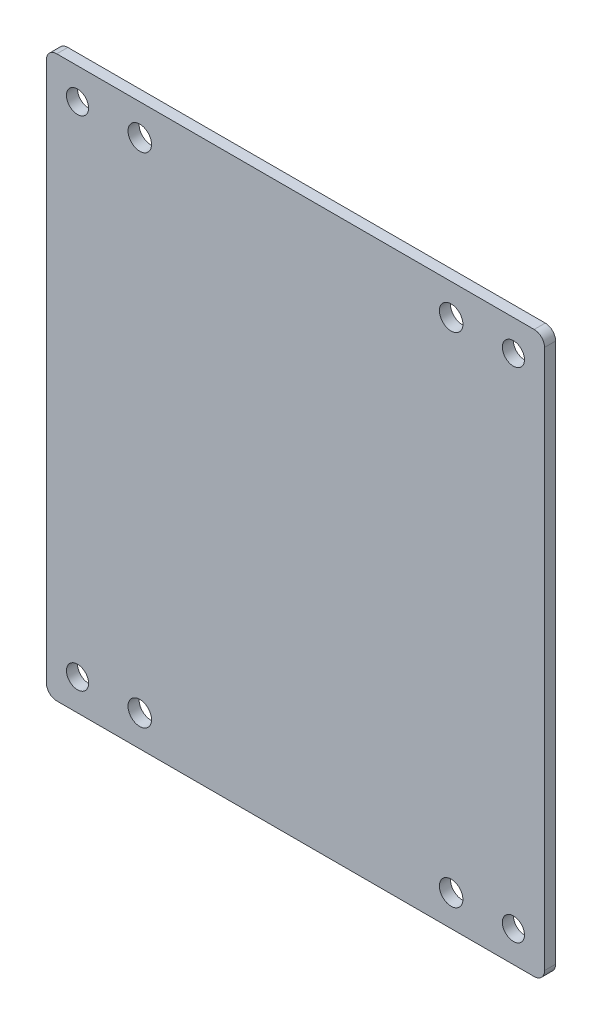
SolidWorks part; units mm, degrees
ref_plane "Alzado" through (0, 0, 0) normal (0, 0, 1) x (1, 0, 0)
ref_plane "Planta" through (0, 0, 0) normal (0, 1, 0) x (1, 0, 0)
ref_plane "Vista lateral" through (0, 0, 0) normal (1, 0, 0) x (0, 0, -1)
sketch "Model" plane through (0, 0, 0) normal (0, 0, 1) x (1, 0, 0)
  line L0 (79.0698, 220.6038) -> (79.0698, 298.6084)
  line L1 (7.0674, 298.6084) -> (7.0674, 220.6038)
  line L2 (8.5674, 219.1038) -> (77.5698, 219.1038)
  line L3 (77.5698, 300.1084) -> (8.5674, 300.1084)
  line L4 (76.4432, 280.3563) -> (73.4432, 280.3563)
  line L5 (76.4432, 232.4763) -> (76.4432, 280.3563)
  line L6 (73.4432, 232.4763) -> (76.4432, 232.4763)
  line L7 (73.4432, 280.3563) -> (73.4432, 232.4763)
  line L8 (28.1808, 232.4801) -> (28.1808, 271.1578)
  line L9 (25.1808, 232.4801) -> (28.1808, 232.4801)
  line L10 (25.1808, 271.1578) -> (25.1808, 232.4801)
  line L11 (9.2551, 269.0104) -> (9.2563, 226.8832)
  line L12 (18.685, 269.0104) -> (18.6863, 226.8832)
  line L13 (18.685, 269.0104) -> (9.2551, 269.0104)
  line L14 (18.6863, 226.8832) -> (9.2563, 226.8832)
  line L15 (37.929, 268.6584) -> (37.9301, 275.5694)
  line L16 (41.2725, 268.3584) -> (38.2289, 268.3584)
  line L17 (41.5725, 277.3009) -> (41.5725, 268.6584)
  line L18 (38.6121, 277.6009) -> (41.2725, 277.6009)
  line L19 (47.8995, 221.0056) -> (62.2048, 221.0056)
  line L20 (62.2048, 228.2055) -> (47.8995, 228.2055)
  line L21 (47.8995, 228.2055) -> (47.8995, 221.0056)
  line L22 (62.2048, 221.0056) -> (62.2048, 228.2055)
  line L23 (28.1941, 221.0056) -> (42.2994, 221.0056)
  line L24 (42.2994, 228.2055) -> (28.1941, 228.2055)
  line L25 (28.1941, 228.2055) -> (28.1941, 221.0056)
  line L26 (42.2994, 221.0056) -> (42.2994, 228.2055)
  line L27 (16.6077, 273.8998) -> (11.5077, 273.8998)
  line L28 (16.6077, 270.7998) -> (16.6077, 273.8998)
  line L29 (11.5077, 270.7998) -> (16.6077, 270.7998)
  line L30 (11.5077, 273.8998) -> (11.5077, 270.7998)
  line L31 (16.6077, 281.0451) -> (11.5077, 281.0451)
  line L32 (16.6077, 277.9451) -> (16.6077, 281.0451)
  line L33 (11.5077, 277.9451) -> (16.6077, 277.9451)
  line L34 (11.5077, 281.0451) -> (11.5077, 277.9451)
  line L35 (25.1808, 271.1578) -> (28.1808, 271.1578)
  line L36 (45.2171, 262.1628) -> (45.7171, 261.6628)
  line L37 (57.5171, 261.6628) -> (58.0171, 262.1628)
  line L38 (45.2171, 269.1628) -> (46.7171, 270.6628)
  line L39 (48.226, 270.6628) -> (46.7171, 270.6628)
  line L40 (45.2171, 269.1628) -> (45.2171, 262.1628)
  line L41 (58.0171, 262.1628) -> (58.0171, 269.1628)
  line L42 (45.7171, 261.6628) -> (57.5171, 261.6628)
  line L43 (57.8731, 273.6225) -> (48.826, 273.6225)
  line L44 (57.1392, 270.0406) -> (57.1392, 272.0907)
  line L45 (48.526, 270.9628) -> (48.526, 273.3225)
  line L46 (48.526, 270.9628) -> (48.226, 270.6628)
  line L47 (48.826, 273.6225) -> (48.526, 273.3225)
  line L48 (58.0171, 269.1628) -> (57.1392, 270.0406)
  line L49 (57.1392, 270.9628) -> (57.1392, 272.5218)
  line L50 (58.1732, 273.9225) -> (58.1739, 278.6843)
  line L51 (61.5165, 272.8218) -> (57.4392, 272.8218)
  line L52 (61.8165, 278.6843) -> (61.8165, 273.1218)
  line L53 (58.774, 278.9843) -> (61.5165, 278.9843)
  line L54 (71.3319, 235.3872) -> (64.3319, 235.3872)
  line L55 (71.3319, 248.1872) -> (71.8319, 247.6872)
  line L56 (71.8319, 235.8872) -> (71.3319, 235.3872)
  line L57 (64.3319, 248.1872) -> (62.8319, 246.6872)
  line L58 (62.8319, 245.1782) -> (62.8319, 246.6872)
  line L59 (64.3319, 248.1872) -> (71.3319, 248.1872)
  line L60 (71.8319, 247.6872) -> (71.8319, 235.8872)
  line L61 (59.8723, 236.5651) -> (59.8723, 244.5782)
  line L62 (63.4541, 236.2651) -> (61.4041, 236.2651)
  line L63 (62.5319, 244.8782) -> (60.1723, 244.8782)
  line L64 (62.5319, 244.8782) -> (62.8319, 245.1782)
  line L65 (59.8723, 244.5782) -> (60.1723, 244.8782)
  line L66 (64.3319, 235.3872) -> (63.4541, 236.2651)
  line L67 (62.5319, 236.2651) -> (60.1723, 236.2651)
  line L68 (59.8723, 236.5651) -> (60.1723, 236.2651)
  line L69 (41.5725, 277.3009) -> (41.2725, 277.6009)
  line L70 (41.5725, 268.6584) -> (41.2725, 268.3584)
  line L71 (38.2289, 268.3584) -> (37.929, 268.6584)
  line L72 (58.1739, 278.6843) -> (58.2618, 278.7722)
  line L73 (58.2618, 278.7722) -> (58.774, 278.9843)
  line L74 (61.5165, 278.9843) -> (61.8165, 278.6843)
  line L75 (61.5165, 272.8218) -> (61.8165, 273.1218)
  line L76 (33.9621, 275.8694) -> (37.6301, 275.8694)
  line L77 (38.3121, 280.2194) -> (38.3121, 277.9009)
  line L78 (38.3121, 277.9009) -> (38.6121, 277.6009)
  line L79 (37.6301, 275.8694) -> (37.9301, 275.5694)
  line L80 (57.8731, 273.6225) -> (58.1732, 273.9225)
  line L81 (57.4392, 272.8218) -> (57.1392, 272.5218)
  arc A0 (8.5674, 300.1084) -> (7.0674, 298.6084) centre (8.5674, 298.6084) ccw
  arc A1 (7.0674, 220.6038) -> (8.5674, 219.1038) centre (8.5674, 220.6038) ccw
  arc A2 (77.5698, 219.1038) -> (79.0698, 220.6038) centre (77.5698, 220.6038) ccw
  arc A3 (79.0698, 298.6084) -> (77.5698, 300.1084) centre (77.5698, 298.6084) ccw
  circle A4 centre (68.3041, 284.2311) radius 1
  circle A5 centre (13.8303, 287.7239) radius 3.7
  circle A6 centre (20.5667, 223.6035) radius 1.7
  circle A7 centre (65.5701, 223.6035) radius 1.7
  circle A8 centre (11.5671, 223.6035) radius 1.6003
  circle A9 centre (74.5698, 223.6035) radius 1.6003
  circle A10 centre (20.5667, 295.6084) radius 1.7
  circle A11 centre (65.5701, 295.6084) radius 1.7
  circle A12 centre (74.5698, 295.6084) radius 1.6003
  circle A13 centre (11.5671, 295.6084) radius 1.6003
  arc A14 (38.3121, 280.2194) -> (33.9621, 275.8694) centre (33.9621, 280.2194) ccw
extrude "Saliente-Extruir1" add sketch "Model" along normal blind 1.6 contours L14 L12 L13 L11 | L35 L10 L9 L8 | L27 L30 L29 L28 | L31 L34 L33 L32 | A5 | L77 A14 L76 L79 L15 L71 L16 L70 L17 L69 L18 L78 | L81 L51 L75 L52 L74 L53 L73 L72 L50 L80 L43 L47 L45 L46 L39 L38 L40 L36 L42 L37 L41 L48 L44 L49 | L61 L68 L67 L62 L66 L54 L56 L60 L55 L59 L57 L58 L64 L63 L65 | L4 L7 L6 L5 | L19 L22 L20 L21 | L23 L26 L24 L25 | L0 A3 L3 A0 L1 A1 L2 A2 A14 L77 L78 L18 L69 L17 L70 L16 L71 L15 L79 L76 A13 A12 A11 A10 A9 A8 A7 A6 A5 A4 L51 L81 L49 L44 L48 L41 L37 L42 | A4
sketch "Croquis2" plane through (0, 0, 1.6) normal (0, 0, 1) x (1, 0, 0)
  line L0 (7.0674, 298.6084) -> (7.0674, 300.1084) construction
  line L1 (7.0674, 300.1084) -> (13.8303, 300.1084) construction
  line L2 (77.5698, 300.1084) -> (8.5674, 300.1084) construction
  line L3 (13.8303, 300.1084) -> (13.8303, 287.7239) construction
  line L4 (7.0674, 219.1038) -> (9.2563, 219.1038) construction
  line L5 (8.5674, 219.1038) -> (77.5698, 219.1038) construction
  line L6 (9.2563, 219.1038) -> (18.6863, 219.1038) construction
  line L7 (18.6863, 219.1038) -> (18.6863, 226.8832) construction
  line L8 (18.6863, 226.8832) -> (18.6863, 269.0104) construction
  line L9 (18.6863, 269.0104) -> (9.2563, 269.0104) construction
  line L10 (9.2563, 269.0104) -> (9.2563, 226.8832) construction
  line L11 (9.2563, 226.8832) -> (18.6863, 226.8832) construction
  line L12 (7.0674, 300.1084) -> (7.0674, 281.0451) construction
  line L13 (7.0674, 298.6084) -> (7.0674, 220.6038) construction
  line L14 (7.0674, 281.0451) -> (7.0674, 277.9451) construction
  line L15 (7.0674, 277.9451) -> (7.0674, 273.8998) construction
  line L16 (7.0674, 273.8998) -> (7.0674, 270.7998) construction
  line L17 (7.0674, 270.7998) -> (11.5077, 270.7998) construction
  line L18 (11.5077, 270.7998) -> (16.6077, 270.7998) construction
  line L19 (16.6077, 270.7998) -> (16.6077, 273.8998) construction
  line L20 (16.6077, 273.8998) -> (11.5077, 273.8998) construction
  line L21 (11.5077, 273.8998) -> (11.5077, 270.7998) construction
  line L22 (11.5077, 277.9451) -> (11.5077, 281.0451) construction
  line L23 (11.5077, 281.0451) -> (16.6077, 281.0451) construction
  line L24 (16.6077, 281.0451) -> (16.6077, 277.9451) construction
  line L25 (16.6077, 277.9451) -> (11.5077, 277.9451) construction
  line L26 (79.0698, 219.1038) -> (79.0698, 221.0056) construction
  line L27 (79.0698, 220.6038) -> (79.0698, 298.6084) construction
  line L28 (79.0698, 221.0056) -> (79.0698, 228.2055) construction
  line L29 (79.0698, 221.0056) -> (62.2048, 221.0056) construction
  line L30 (62.2048, 221.0056) -> (47.8995, 221.0056) construction
  line L31 (47.8995, 221.0056) -> (42.2994, 221.0056) construction
  line L32 (42.2994, 221.0056) -> (28.1941, 221.0056) construction
  line L33 (28.1941, 221.0056) -> (28.1941, 228.2055) construction
  line L34 (28.1941, 228.2055) -> (42.2994, 228.2055) construction
  line L35 (42.2994, 228.2055) -> (42.2994, 221.0056) construction
  line L36 (47.8995, 221.0056) -> (47.8995, 228.2055) construction
  line L37 (62.2048, 228.2055) -> (62.2048, 221.0056) construction
  line L38 (47.8995, 228.2055) -> (62.2048, 228.2055) construction
  line L39 (79.0698, 219.1038) -> (79.0698, 232.4763) construction
  line L40 (79.0698, 232.4763) -> (79.0698, 280.3563) construction
  line L41 (79.0698, 280.3563) -> (76.4432, 280.3563) construction
  line L42 (76.4432, 280.3563) -> (73.4432, 280.3563) construction
  line L43 (76.4432, 280.3563) -> (76.4432, 232.4763) construction
  line L44 (76.4432, 232.4763) -> (73.4432, 232.4763) construction
  line L45 (73.4432, 232.4763) -> (73.4432, 280.3563) construction
  line L46 (73.4432, 232.4763) -> (28.1808, 232.4763) construction
  line L47 (28.1808, 232.4763) -> (25.1808, 232.4763) construction
  line L48 (28.1808, 232.4763) -> (28.1808, 271.1539) construction
  line L49 (28.1808, 271.1539) -> (25.1808, 271.1539) construction
  line L50 (25.1808, 271.1539) -> (25.1808, 232.4763) construction
  circle A0 centre (13.8303, 287.7239) radius 3.7
  dimension "D3" = 7.4
  dimension "D14" = 1.9018
  dimension "D1" = 6.7629
  dimension "D2" = 12.3846
  dimension "D4" = 2.1889
  dimension "D5" = 9.43
  dimension "D6" = 7.7794
  dimension "D7" = 42.1272
  dimension "D8" = 19.0633
  dimension "D9" = 3.1
  dimension "D10" = 3.1
  dimension "D11" = 4.0454
  dimension "D12" = 4.4403
  dimension "D13" = 5.1
  dimension "D15" = 7.1999
  dimension "D16" = 16.865
  dimension "D17" = 14.3053
  dimension "D18" = 5.6001
  dimension "D19" = 14.1053
  dimension "D20" = 13.3724
  dimension "D21" = 2.6266
  dimension "D22" = 3
  dimension "D23" = 45.2624
  dimension "D24" = 3
  dimension "D25" = 38.6776
